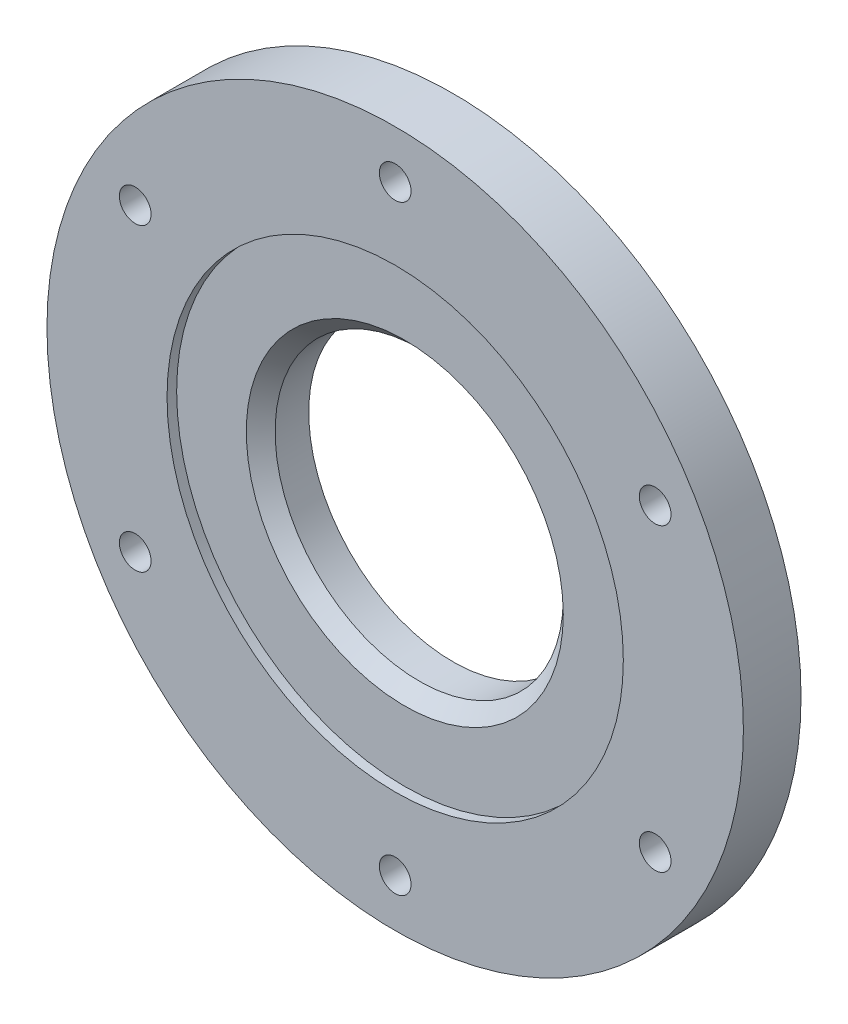
SolidWorks part; units mm, degrees
material "Plain Carbon Steel"
ref_plane "Front Plane" through (0, 0, 0) normal (0, 0, 1) x (1, 0, 0)
ref_plane "Top Plane" through (0, 0, 0) normal (0, 1, 0) x (1, 0, 0)
ref_plane "Right Plane" through (0, 0, 0) normal (1, 0, 0) x (0, 0, -1)
sketch "Sketch1" plane through (0, 0, 0) normal (0, 0, 1) x (1, 0, 0)
  circle A0 centre (0, 0) radius 30
  circle A1 centre (0, 0) radius 72.5
  dimension "D1" = 60
  dimension "D2" = 145
extrude "Boss-Extrude1" add sketch "Sketch1" against normal blind 12
hole_wizard "M6 Clearance Hole1" positions "Sketch3" profile "Sketch2" hole size "M6" standard "Peddi DIN" end condition through all
sketch "Sketch3" plane through (9.5461, 92.531, -12) normal (0, 0, 1) x (1, 0, 0)
  circle A0 centre (-9.5461, -92.531) radius 62.5
  point P0 (-9.5461, -30.031)
  dimension "D1" = 125
sketch "Sketch2" plane through (0, 62.5, -12) normal (1, 0, 0) x (0, 1, 0)
  line L0 (0, 0) -> (0, 12)
  line L1 (0, 12) -> (3.3, 12)
  line L2 (3.3, 12) -> (3.3, 0)
  line L5 (3.3, 0) -> (0, 0)
  line L11 (0, -6.35) -> (0, 107.95) construction
  dimension "Thru Hole Dia." = 6.6
  dimension "Thru Hole Depth" = 12
pattern_circular "CirPattern1" count 6 every 60 about axis through (0, 0, 0) along (0, 0, 1) of "M6 Clearance Hole1"
sketch "Sketch4" plane through (0, 0, 0) normal (0, 0, 1) x (1, 0, 0)
  circle A1 centre (0, 0) radius 47.5
  dimension "D2" = 95
extrude "Cut-Extrude1" cut sketch "Sketch4" against normal blind 2
chamfer "Chamfer1" distance 3 angle 45 1 edges at (30, 0, -2)
other "Freeze***"
